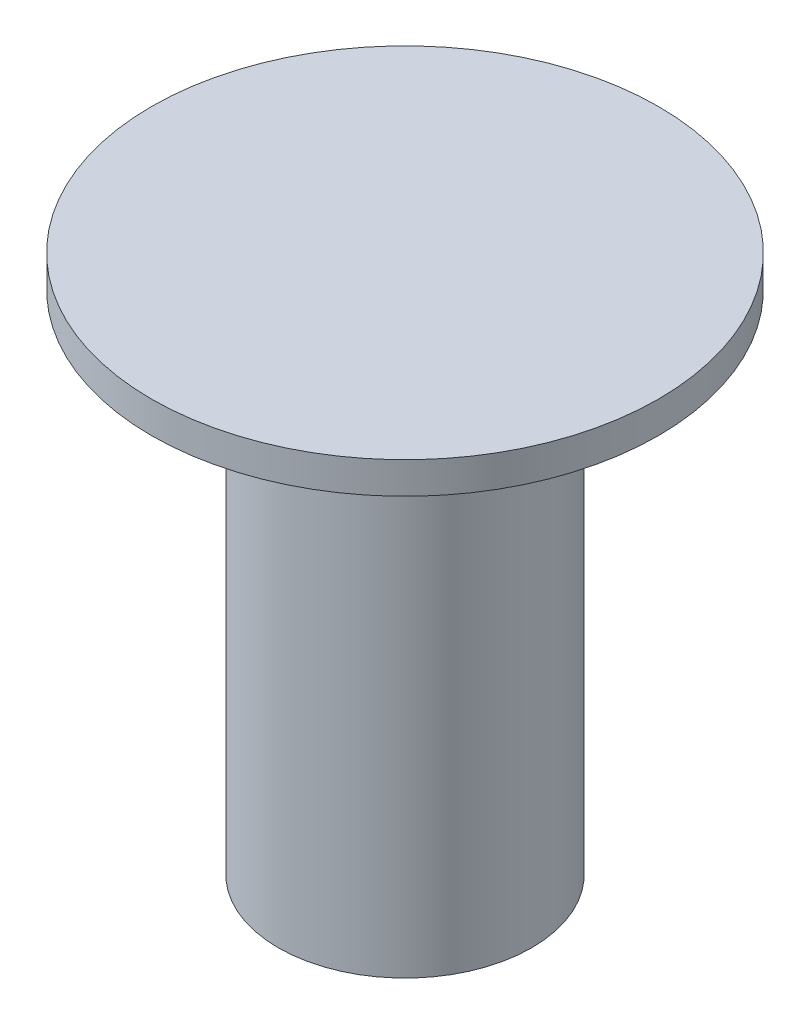
SolidWorks part; units mm, degrees
ref_plane "前视基准面" through (0, 0, 0) normal (0, 0, 1) x (1, 0, 0)
ref_plane "上视基准面" through (0, 0, 0) normal (0, 1, 0) x (1, 0, 0)
ref_plane "右视基准面" through (0, 0, 0) normal (1, 0, 0) x (0, 0, -1)
other "Configuration Table"
sketch "草图1" plane through (0, 0, 0) normal (0, 1, 0) x (1, 0, 0)
  circle A0 centre (0, 0) radius 8
  dimension "D1" = 16
extrude "凸台-拉伸1" add sketch "草图1" along normal blind 32
sketch "草图2" plane through (0, 32, 0) normal (0, 1, 0) x (1, 0, 0)
  circle A0 centre (0, 0) radius 16
  dimension "D1" = 32
extrude "凸台-拉伸2" add sketch "草图2" along normal blind 2
